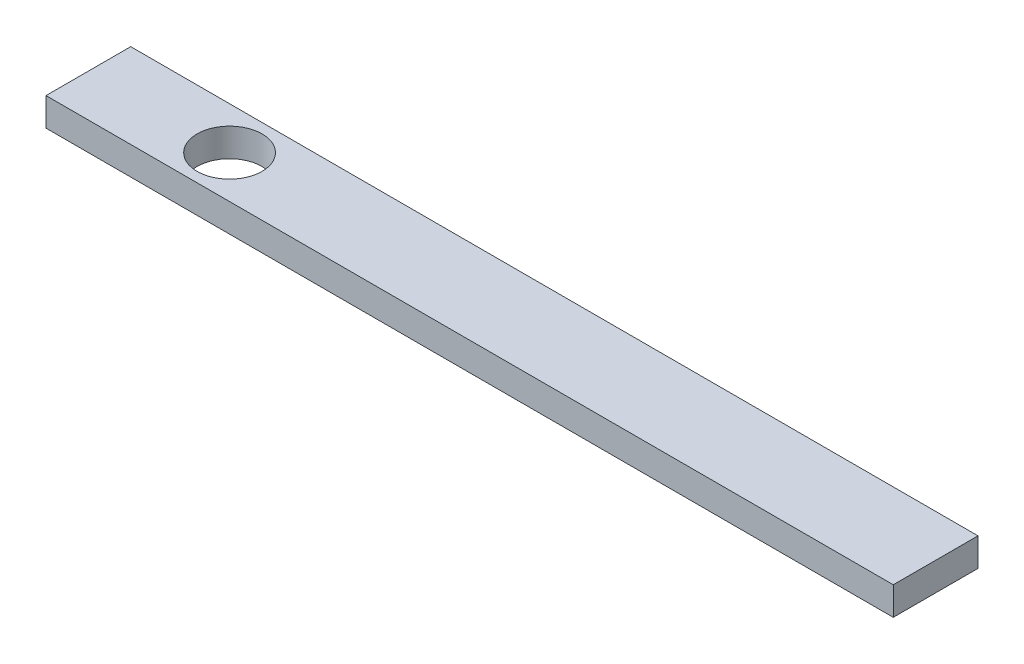
SolidWorks part; units mm, degrees
ref_plane "Front Plane" through (0, 0, 0) normal (0, 0, 1) x (1, 0, 0)
ref_plane "Top Plane" through (0, 0, 0) normal (0, 1, 0) x (1, 0, 0)
ref_plane "Right Plane" through (0, 0, 0) normal (1, 0, 0) x (0, 0, -1)
sketch "Sketch1" plane through (0, 0, 0) normal (0, 1, 0) x (1, 0, 0)
  line L0 (0, 0) -> (0, 7.62)
  line L1 (0, 7.62) -> (76.2, 7.62)
  line L2 (0, 0) -> (76.2, 0)
  line L3 (76.2, 0) -> (76.2, 7.62)
  circle A0 centre (12.7, 3.81) radius 2.921
  dimension "D3" = 5.842
  dimension "D1" = 7.62
  dimension "D2" = 76.2
  dimension "D4" = 3.81
  dimension "D5" = 12.7
extrude "Boss-Extrude1" add sketch "Sketch1" along normal blind 2.54 contours L2 L3 L1 L0
